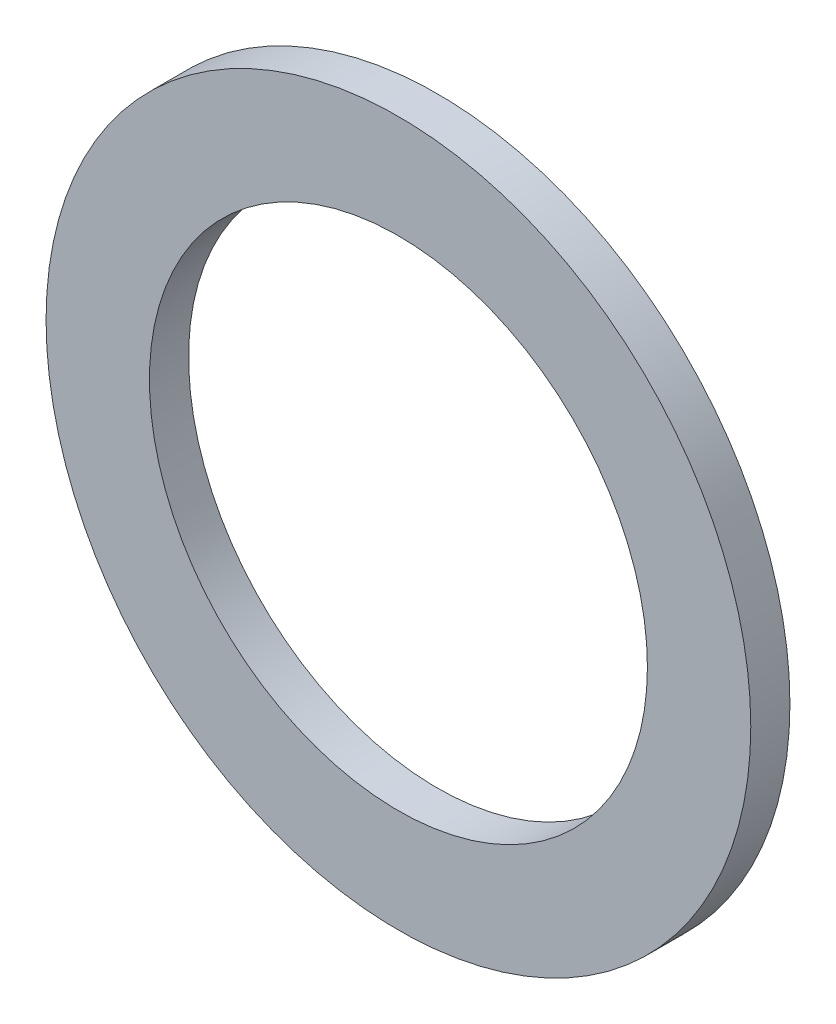
SolidWorks part; units mm, degrees
ref_plane "Front Plane" through (0, 0, 0) normal (0, 0, 1) x (1, 0, 0)
ref_plane "Top Plane" through (0, 0, 0) normal (0, 1, 0) x (1, 0, 0)
ref_plane "Right Plane" through (0, 0, 0) normal (1, 0, 0) x (0, 0, -1)
sketch "Sketch1" plane through (0, 0, 0) normal (0, 0, 1) x (1, 0, 0)
  circle A0 centre (0, 0) radius 4.5
  circle A1 centre (0, 0) radius 3.18
  dimension "D1" = 9
  dimension "D2" = 6.36
extrude "Boss-Extrude1" add sketch "Sketch1" along normal blind 0.5
